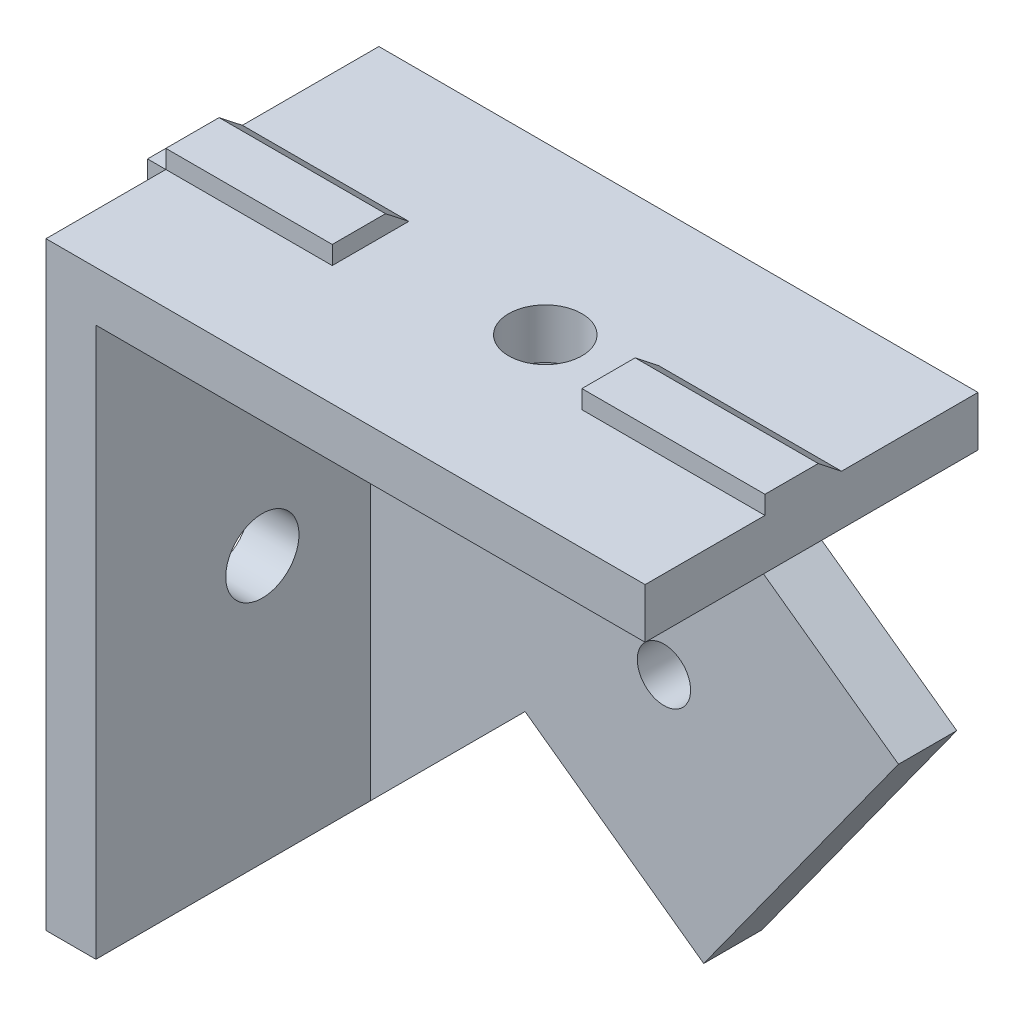
SolidWorks part; units mm, degrees
material "ABS"
ref_plane "Front Plane" through (0, 0, 0) normal (0, 0, 1) x (1, 0, 0)
ref_plane "Top Plane" through (0, 0, 0) normal (0, 1, 0) x (1, 0, 0)
ref_plane "Right Plane" through (0, 0, 0) normal (1, 0, 0) x (0, 0, -1)
sketch "Sketch1" plane through (0, 0, 0) normal (0, 0, 1) x (1, 0, 0)
  line L0 (0, -36) -> (0, 0)
  line L1 (0, 0) -> (36, 0)
  line L2 (36, 0) -> (36, -3)
  line L3 (36, -3) -> (3, -36)
  line L4 (3, -36) -> (0, -36)
  dimension "D1" = 36
  dimension "D2" = 36
  dimension "D3" = 3
  dimension "D4" = 3
extrude "Boss-Extrude1" add sketch "Sketch1" along normal blind 3.5
sketch "Sketch2" plane through (0, 0, 3.5) normal (0, 0, 1) x (1, 0, 0)
  line L0 (0, -36) -> (0, 0)
  line L1 (0, 0) -> (36, 0)
  line L2 (36, 0) -> (36, -3)
  line L3 (36, -3) -> (3, -3)
  line L4 (3, -3) -> (3, -36)
  line L5 (3, -36) -> (0, -36)
extrude "Boss-Extrude2" add sketch "Sketch2" along normal blind 16.5
sketch "Sketch4" plane through (0, -3, 0) normal (0, -1, 0) x (1, 0, 0)
  line L0 (36, 20) -> (36, 3.5) construction
  line L1 (3, 0) -> (36, 0) construction
  circle A0 centre (20, 10) radius 2.2
  dimension "D1" = 4.4
  dimension "D2" = 16
  dimension "D3" = 10
extrude "Cut-Extrude1" cut sketch "Sketch4" against normal through all
sketch "Sketch5" plane through (3, 0, 0) normal (1, 0, 0) x (0, 0, -1)
  line L0 (0, -36) -> (0, -3) construction
  line L1 (-20, -36) -> (-3.5, -36) construction
  circle A0 centre (-10, -20) radius 2.2
  dimension "D1" = 10
  dimension "D2" = 4.4
  dimension "D3" = 16
extrude "Cut-Extrude2" cut sketch "Sketch5" against normal through all
sketch "Sketch6" plane through (36, 0, 0) normal (1, 0, 0) x (0, 0, -1)
  line L0 (-12.8, 0) -> (-12.8, 1.1)
  line L1 (-20, 0) -> (0, 0) construction
  line L2 (-12.8, 1.1) -> (-9.6, 1.1)
  line L3 (-9.6, 1.1) -> (-8.2, 0)
  line L4 (-8.2, 0) -> (-12.8, 0)
  line L5 (-20, -3) -> (-20, 0) construction
  dimension "D1" = 1.1
  dimension "D2" = 3.2
  dimension "D3" = 7.2
  dimension "D4" = 4.6
extrude "Boss-Extrude5" add sketch "Sketch6" against normal through all
sketch "Sketch7" plane through (0, 0, 12.8) normal (0, 0, 1) x (1, 0, 0)
  line L0 (0, 1.1) -> (36, 1.1) construction
  line L1 (25, 1.1) -> (10, 1.1)
  line L2 (25, 1.1) -> (25, 0)
  line L3 (25, 0) -> (10, 0)
  line L4 (10, 1.1) -> (10, 0)
  line L5 (0, 0) -> (36, 0) construction
  line L6 (36, 1.1) -> (36, 0) construction
  dimension "D1" = 11
  dimension "D2" = 15
extrude "Cut-Extrude3" cut sketch "Sketch7" against normal through all
sketch "Sketch8" plane through (0, -36, 0) normal (0, -1, 0) x (1, 0, 0)
  line L0 (0, 8.2) -> (0, 12.8)
  line L1 (0, 20) -> (0, 0) construction
  line L2 (0, 12.8) -> (-1.1, 12.8)
  line L3 (-1.1, 12.8) -> (-1.1, 9.6)
  line L4 (-1.1, 9.6) -> (0, 8.2)
  line L5 (0, 20) -> (3, 20) construction
  dimension "D1" = 1.1
  dimension "D2" = 3.2
  dimension "D3" = 7.2
  dimension "D4" = 4.6
extrude "Boss-Extrude6" add sketch "Sketch8" against normal up to surface (36 mm away) up to face at (16.0833, 0, 11.6167)
sketch "Sketch9" plane through (0, 0, 12.8) normal (0, 0, 1) x (1, 0, 0)
  line L0 (0, 0) -> (0, -36) construction
  line L1 (0, -10) -> (-1.1, -10)
  line L2 (0, -10) -> (0, -25)
  line L3 (0, -25) -> (-1.1, -25)
  line L4 (-1.1, -10) -> (-1.1, -25)
  line L5 (-1.1, 0) -> (-1.1, -36) construction
  line L6 (0, -36) -> (-1.1, -36) construction
  dimension "D1" = 15
  dimension "D2" = 11
extrude "Cut-Extrude4" cut sketch "Sketch9" against normal through all
sketch "Sketch10" plane through (0, 0, 3.5) normal (0, 0, 1) x (1, 0, 0)
  line L0 (12.2864, -26.7136) -> (26.6124, -12.3876)
  line L1 (3, -36) -> (36, -3) construction
  line L2 (26.6124, -12.3876) -> (34.7219, -18.2387)
  line L3 (34.7219, -18.2387) -> (23.0197, -34.4578)
  line L4 (23.0197, -34.4578) -> (12.2864, -26.7136)
  line L7 (3, -3) -> (36, -3) construction
  dimension "D1" = 20
  dimension "D2" = 10
  dimension "D3" = 80.811
  dimension "D4" = 9.3876
extrude "Boss-Extrude7" add sketch "Sketch10" against normal up to surface (3.5 mm away) up to face at (15, -15, 0)
sketch "Sketch11" plane through (0, 0, 3.5) normal (0, 0, 1) x (1, 0, 0)
  line L0 (23.0197, -34.4578) -> (34.7219, -18.2387) construction
  line L2 (12.2864, -26.7136) -> (23.0197, -34.4578) construction
  circle A0 centre (20.6297, -20.6297) radius 1.6
  dimension "D1" = 3.2
  dimension "D2" = 10.0291
  dimension "D3" = 9.8155
extrude "Cut-Extrude5" cut sketch "Sketch11" against normal through all
